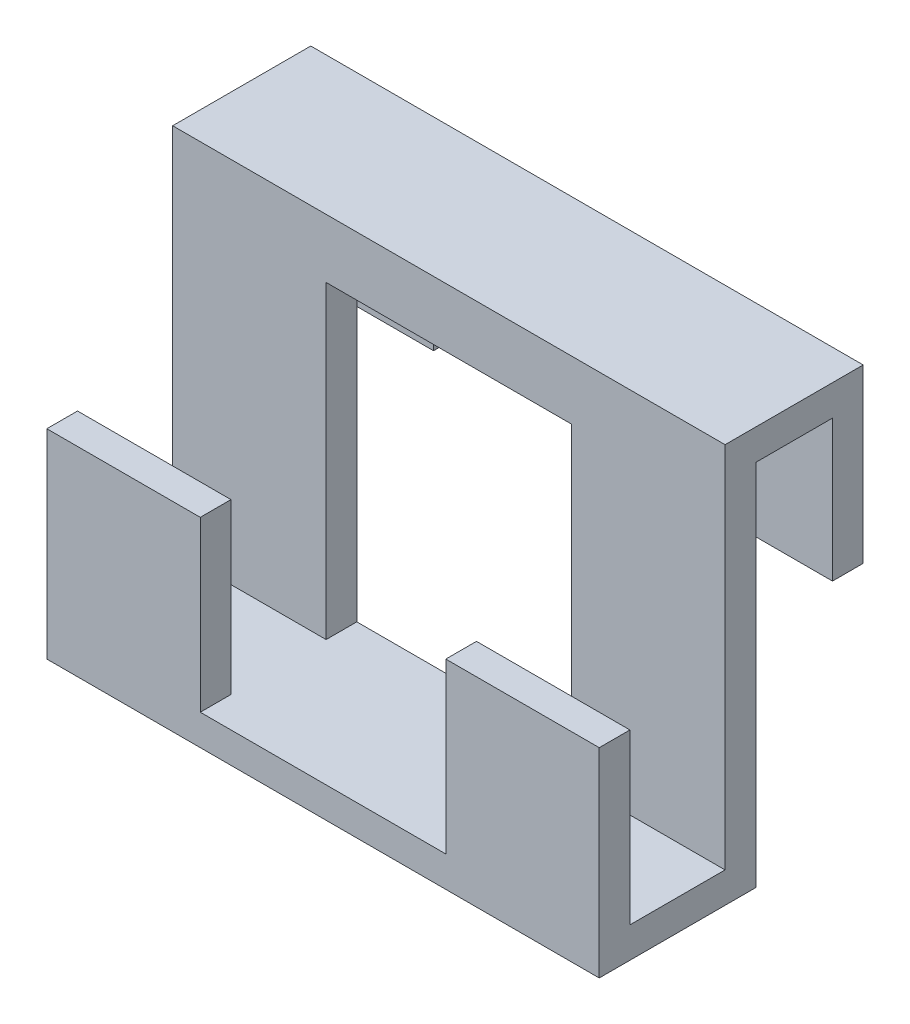
SolidWorks part; units mm, degrees
ref_plane "Front Plane" through (0, 0, 0) normal (0, 0, 1) x (1, 0, 0)
ref_plane "Top Plane" through (0, 0, 0) normal (0, 1, 0) x (1, 0, 0)
ref_plane "Right Plane" through (0, 0, 0) normal (1, 0, 0) x (0, 0, -1)
sketch "Sketch1" plane through (0, 0, 0) normal (1, 0, 0) x (0, 0, -1)
  line L0 (51.8241, -3.9391) -> (51.8241, 52.0609)
  line L1 (51.8241, 52.0609) -> (6.8241, 52.0609)
  line L2 (6.8241, 52.0609) -> (6.8241, -77.9391)
  line L3 (6.8241, -77.9391) -> (16.8241, -77.9391)
  line L4 (16.8241, -77.9391) -> (16.8241, 42.0609)
  line L5 (16.8241, 42.0609) -> (41.8241, 42.0609)
  line L6 (41.8241, 42.0609) -> (41.8241, -3.9391)
  line L7 (41.8241, -3.9391) -> (51.8241, -3.9391)
  line L8 (6.8241, -77.9391) -> (-34.1759, -77.9391)
  line L9 (-34.1759, -77.9391) -> (-34.1759, -12.9391)
  line L10 (-34.1759, -12.9391) -> (-24.1759, -12.9391)
  line L11 (-24.1759, -12.9391) -> (-24.1759, -67.9391)
  line L12 (-24.1759, -67.9391) -> (6.8241, -67.9391)
  dimension "D1" = 10
  dimension "D2" = 10
  dimension "D3" = 25
  dimension "D4" = 120
  dimension "D5" = 46
  dimension "D6" = 10
  dimension "D7" = 10
  dimension "D8" = 31
  dimension "D9" = 10
  dimension "D10" = 65
extrude "Boss-Extrude1" add sketch "Sketch1" along normal blind 180 contours L6 L7 L0 L1 L2 L3 L4 L5 | L12 L11 L10 L9 L8 L2
sketch "Sketch3" plane through (0, 0, -6.8241) normal (0, 0, 1) x (1, 0, 0)
  line L1 (50, 32.8455) -> (130, 32.8455)
  line L2 (50, 32.8455) -> (50, -67.9391)
  line L3 (50, -67.9391) -> (130, -67.9391)
  line L4 (130, 32.8455) -> (130, -67.9391)
  line L5 (0, 52.0609) -> (0, -67.9391) construction
  line L6 (180, 52.0609) -> (180, -67.9391) construction
  dimension "D1" = 50
  dimension "D2" = 50
  dimension "D3" = 100.7846
extrude "Cut-Extrude1" cut sketch "Sketch3" against normal through all both and the other way through all contours L1 L4 L3 L2
